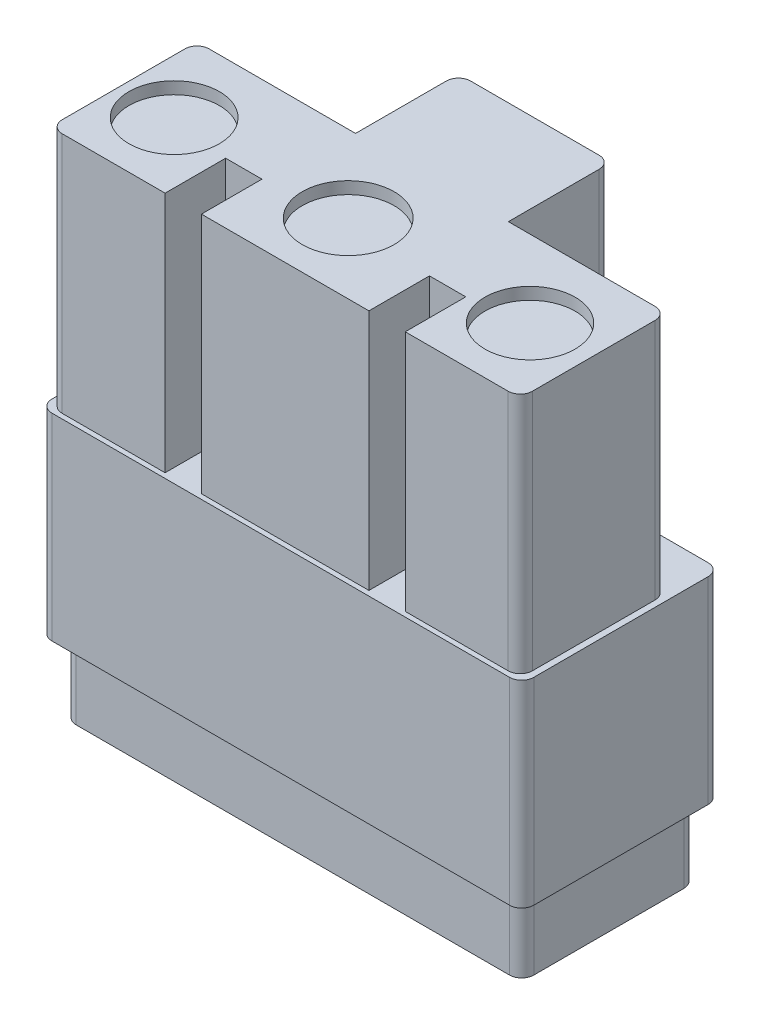
SolidWorks part; units mm, degrees
ref_plane "正面" through (0, 0, 0) normal (0, 0, 1) x (1, 0, 0)
ref_plane "平面" through (0, 0, 0) normal (0, 1, 0) x (1, 0, 0)
ref_plane "右側面" through (0, 0, 0) normal (1, 0, 0) x (0, 0, -1)
sketch "ｽｹｯﾁ1" plane through (0, 0, 0) normal (0, 1, 0) x (1, 0, 0)
  line L1 (0, 0) -> (39.8, 0)
  line L2 (0, 0) -> (0, 16.4)
  line L3 (0, 16.4) -> (39.8, 16.4)
  line L4 (39.8, 0) -> (39.8, 16.4)
  dimension "D1" = 39.8
  dimension "D2" = 16.4
extrude "ﾎﾞｽ - 押し出し1" add sketch "ｽｹｯﾁ1" along normal blind 16.3
sketch "ｽｹｯﾁ2" plane through (0, 0, 0) normal (0, -1, 0) x (1, 0, 0)
  line L8 (1, -1) -> (1, -15.4)
  line L9 (1, -15.4) -> (38.8, -15.4)
  line L10 (38.8, -15.4) -> (38.8, -1)
  line L11 (38.8, -1) -> (1, -1)
  line L12 (1, -1) -> (1, -15.4)
  line L13 (1, -15.4) -> (38.8, -15.4)
  line L14 (38.8, -15.4) -> (38.8, -1)
  line L15 (38.8, -1) -> (1, -1)
  dimension "D1" = 1
extrude "ﾎﾞｽ - 押し出し2" add sketch "ｽｹｯﾁ2" along normal blind 6
sketch "ｽｹｯﾁ3" plane through (0, 16.3, 0) normal (0, 1, 0) x (1, 0, 0)
  line L1 (0.4447, 0.4065) -> (39.2794, 0.4065)
  line L2 (0.4447, 0.4065) -> (0.4447, 12.5424)
  line L3 (0.4447, 12.5424) -> (39.2794, 12.5424)
  line L4 (39.2794, 0.4065) -> (39.2794, 12.5424)
extrude "ﾎﾞｽ - 押し出し3" add sketch "ｽｹｯﾁ3" along normal blind 20
sketch "ｽｹｯﾁ4" plane through (0, 0, -12.5424) normal (0, 0, -1) x (-1, 0, 0)
  line L0 (-39.2794, 36.3) -> (-0.4447, 36.3) construction
  line L1 (-26.1594, 36.3) -> (-13.5363, 36.3)
  line L2 (-26.1594, 36.3) -> (-26.1594, -6)
  line L3 (-26.1594, -6) -> (-13.5363, -6)
  line L4 (-13.5363, 36.3) -> (-13.5363, -6)
  line L5 (-1, -6) -> (-38.8, -6) construction
extrude "ﾎﾞｽ - 押し出し4" add sketch "ｽｹｯﾁ4" along normal blind 8.5
sketch "ｽｹｯﾁ5" plane through (0, 0, -0.4065) normal (0, 0, 1) x (1, 0, 0)
  line L0 (0.4447, 36.3) -> (39.2794, 36.3) construction
  line L1 (9.9447, 36.3) -> (12.9447, 36.3)
  line L2 (9.9447, 36.3) -> (9.9447, 16.3)
  line L3 (9.9447, 16.3) -> (12.9447, 16.3)
  line L4 (12.9447, 36.3) -> (12.9447, 16.3)
  line L5 (0, 16.3) -> (39.8, 16.3) construction
  line L6 (0.4447, 36.3) -> (0.4447, 16.3) construction
  line L7 (19.8621, 36.3) -> (19.8621, 16.3) construction
  line L8 (0.4447, 16.3) -> (39.2794, 16.3) construction
  line L9 (29.7794, 16.3) -> (26.7794, 16.3)
  line L10 (26.7794, 36.3) -> (26.7794, 16.3)
  line L11 (29.7794, 36.3) -> (29.7794, 16.3)
  line L12 (29.7794, 36.3) -> (26.7794, 36.3)
  dimension "D1" = 9.5
  dimension "D2" = 3
extrude "ｶｯﾄ - 押し出し2" cut sketch "ｽｹｯﾁ5" against normal blind 5
sketch "ｽｹｯﾁ6" plane through (0, 36.3, 0) normal (0, 1, 0) x (1, 0, 0)
  circle A0 centre (4.9198, 6.1788) radius 3.7346
  circle A1 centre (19.2932, 6.1788) radius 3.7932
  circle A2 centre (34.3113, 6.1788) radius 3.7224
extrude "ｶｯﾄ - 押し出し3" cut sketch "ｽｹｯﾁ6" against normal blind 1
sketch "ｽｹｯﾁ7" plane through (0, -6, 0) normal (0, -1, 0) x (1, 0, 0)
  circle A0 centre (6.8919, -8.075) radius 3.9062
  circle A1 centre (19.0657, -8.075) radius 3.8153
  circle A2 centre (32.1875, -8.075) radius 3.6863
extrude "ｶｯﾄ - 押し出し4" cut sketch "ｽｹｯﾁ7" against normal blind 1
fillet "ﾌｨﾚｯﾄ1" radius 1 14 edges at (1, -3, -15.4) (0, 8.15, -16.4) (0.4447, 26.3, -12.5424) (0.4447, 26.3, -0.4065) (0, 8.15, 0) (1, -3, -1) (38.8, -3, -1) (39.8, 8.15, 0) (39.2794, 26.3, -0.4065) (39.2794, 26.3, -12.5424) (39.8, 8.15, -16.4) (38.8, -3, -15.4) (26.1594, 15.15, -21.0424) (13.5363, 15.15, -21.0424)
